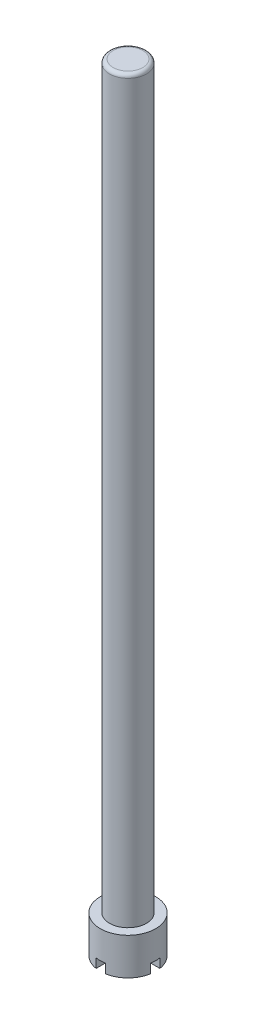
SolidWorks part; units mm, degrees
ref_plane "Front Plane" through (0, 0, 0) normal (0, 0, 1) x (1, 0, 0)
ref_plane "Top Plane" through (0, 0, 0) normal (0, 1, 0) x (1, 0, 0)
ref_plane "Right Plane" through (0, 0, 0) normal (1, 0, 0) x (0, 0, -1)
sketch "Sketch1" plane through (0, 0, 0) normal (0, 1, 0) x (1, 0, 0)
  circle A0 centre (0, 0) radius 0.5
  dimension "D1" = 1
extrude "Boss-Extrude1" add sketch "Sketch1" along normal blind 20 contours A0
sketch "Sketch2" plane through (0, 0, 0) normal (0, -1, 0) x (1, 0, 0)
  circle A0 centre (0, 0) radius 0.75
  circle A1 centre (0, 0) radius 0.5 construction
  dimension "D1" = 0.25
extrude "Boss-Extrude2" add sketch "Sketch2" along normal blind 1 contours A0
sketch "Sketch3" plane through (0, -1, 0) normal (0, -1, 0) x (1, 0, 0)
  line L0 (-0.8035, 0) -> (0.9789, 0) construction
  line L1 (0, 0.776) -> (0, -0.8025) construction
  line L2 (-0.125, 0.125) -> (-0.8755, 0.125)
  line L3 (0.125, -0.8351) -> (-0.125, -0.8351)
  line L4 (0.125, -0.8351) -> (0.125, -0.125)
  line L5 (0.125, 0.8351) -> (-0.125, 0.8351)
  line L6 (-0.125, -0.8351) -> (-0.125, -0.125)
  line L7 (0.125, -0.8351) -> (-0.125, 0.8351) construction
  line L8 (0.125, 0.8351) -> (-0.125, -0.8351) construction
  line L9 (0.8755, -0.125) -> (0.125, -0.125)
  line L10 (0.8755, -0.125) -> (0.8755, 0.125)
  line L11 (0.8755, 0.125) -> (0.125, 0.125)
  line L12 (-0.8755, -0.125) -> (-0.8755, 0.125)
  line L13 (0.8755, -0.125) -> (-0.8755, 0.125) construction
  line L14 (0.8755, 0.125) -> (-0.8755, -0.125) construction
  line L15 (-0.125, 0.125) -> (-0.125, 0.8351)
  line L19 (-0.125, -0.125) -> (-0.8755, -0.125)
  line L21 (0.125, 0.125) -> (0.125, 0.8351)
  point P5 (0, 0)
  point P10 (0, 0)
  dimension "D1" = 0.25
  dimension "D2" = 0.25
extrude "Cut-Extrude1" cut sketch "Sketch3" against normal blind 0.25 contours L2 L12 L19 L6 L3 L4 L9 L10 L11 L21 L5 L15
sketch "Sketch5" plane through (0, 0, 0) normal (1, 0, 0) x (0, 0, -1)
  line L0 (0, -0.659) -> (0, -1)
  line L1 (0, -1) -> (0.25, -1)
  line L2 (0.125, -1) -> (0.7395, -1) construction
  line L3 (0.25, -1) -> (0.25, -0.75)
  line L4 (0.25, -0.75) -> (0, -0.659)
  line L5 (-0.125, -0.75) -> (0.125, -0.75) construction
  line L6 (0, -0.659) -> (0, 1.1818) construction
  dimension "D1" = 0.25
  dimension "D2" = 0.25
  dimension "D3" = 20
revolve "Cut-Revolve1" cut sketch "Sketch5" angle 360 about L6
fillet "Fillet1" radius 0.1 1 edges at (0, 20, 0.5)
